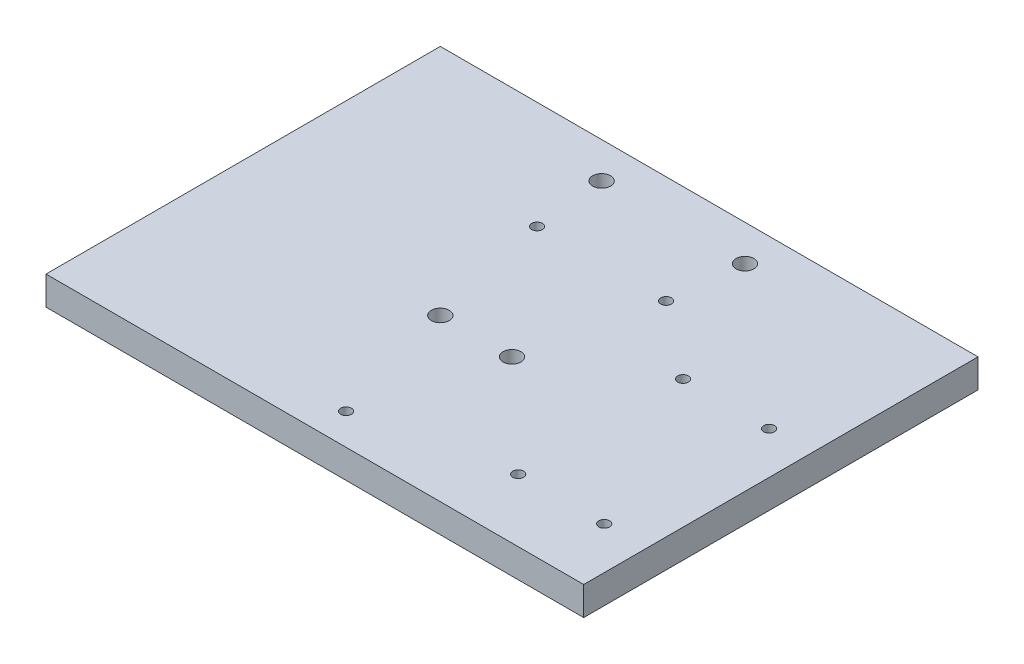
SolidWorks part; units mm, degrees
ref_plane "Front Plane" through (0, 0, 0) normal (0, 0, 1) x (1, 0, 0)
ref_plane "Top Plane" through (0, 0, 0) normal (0, 1, 0) x (1, 0, 0)
ref_plane "Right Plane" through (0, 0, 0) normal (1, 0, 0) x (0, 0, -1)
sketch "Sketch1" plane through (0, 0, 0) normal (0, 1, 0) x (1, 0, 0)
  line L0 (-75, 0) -> (75, 0)
  line L1 (-75, 0) -> (-75, -110)
  line L2 (-75, -110) -> (75, -110)
  line L3 (75, -110) -> (75, 0)
  line L4 (0, 0) -> (0, -20) construction
  line L5 (10, -20) -> (-10, -20) construction
  line L6 (-10, -20) -> (-10, -65) construction
  line L7 (10, -20) -> (10, -65) construction
  line L8 (0, -10) -> (-20, -10) construction
  circle A1 centre (-10, -65) radius 2.5
  circle A2 centre (10, -65) radius 2.5
  circle A3 centre (-20, -10) radius 2.5
  circle A4 centre (20, -10) radius 2.5
  point P4 (0, 0)
  dimension "D6" = 5
  dimension "D7" = 5
  dimension "D11" = 5
  dimension "D1" = 150
  dimension "D2" = 110
  dimension "D3" = 20
  dimension "D4" = 10
  dimension "D8" = 45
  dimension "D9" = 45
  dimension "D10" = 20
extrude "Boss-Extrude1" add sketch "Sketch1" along normal blind 8
sketch "Sketch3" plane through (0, 8, 0) normal (0, 1, 0) x (1, 0, 0)
  line L0 (0, 0) -> (0, -30) construction
  line L2 (18, -30) -> (-18, -30) construction
  line L3 (75, 0) -> (-75, 0) construction
  line L4 (0, -30) -> (0, -101.3) construction
  circle A0 centre (-18, -30) radius 1.5
  circle A1 centre (18, -30) radius 1.5
  circle A2 centre (0, -101.3) radius 1.5
  point P8 (0, -30)
  dimension "D3" = 3
  dimension "D5" = 3
  dimension "D1" = 18
  dimension "D2" = 30
  dimension "D4" = 71.3
extrude "Cut-Extrude1" cut sketch "Sketch3" against normal blind 8
sketch "Sketch4" plane through (0, 8, 0) normal (0, 1, 0) x (1, 0, 0)
  line L0 (0, 0) -> (0, -46.4925) construction
  line L1 (0, -46.4925) -> (39.2157, -46.4925) construction
  line L2 (39.2157, -46.4925) -> (63.2157, -46.4925) construction
  line L3 (0, -46.4925) -> (0, -92.4925) construction
  line L4 (0, -92.4925) -> (63.2157, -92.4925) construction
  line L5 (39.2157, -46.4925) -> (39.2157, -92.4925) construction
  circle A0 centre (39.2157, -46.4925) radius 1.5
  circle A1 centre (63.2157, -46.4925) radius 1.5
  circle A2 centre (39.2157, -92.4925) radius 1.5
  circle A3 centre (63.2157, -92.4925) radius 1.5
  dimension "D1" = 3
  dimension "D2" = 3
  dimension "D5" = 3
  dimension "D6" = 3
  dimension "D3" = 24
  dimension "D4" = 46
extrude "Cut-Extrude2" cut sketch "Sketch4" against normal blind 8
sketch "Sketch5" plane through (0, 0, 0) normal (0, -1, 0) x (1, 0, 0)
  line L1 (-5, 96.3) -> (5, 96.3)
  line L2 (-5, 96.3) -> (-5, 106.3)
  line L3 (-5, 106.3) -> (5, 106.3)
  line L4 (5, 96.3) -> (5, 106.3)
  line L5 (-5, 96.3) -> (5, 106.3) construction
  line L6 (-5, 106.3) -> (5, 96.3) construction
  line L7 (34.2157, 87.4925) -> (44.2157, 87.4925)
  line L8 (34.2157, 87.4925) -> (34.2157, 97.4925)
  line L9 (34.2157, 97.4925) -> (44.2157, 97.4925)
  line L10 (44.2157, 87.4925) -> (44.2157, 97.4925)
  line L11 (34.2157, 87.4925) -> (44.2157, 97.4925) construction
  line L12 (34.2157, 97.4925) -> (44.2157, 87.4925) construction
  line L13 (58.2157, 87.4925) -> (68.2157, 87.4925)
  line L14 (58.2157, 87.4925) -> (58.2157, 97.4925)
  line L15 (58.2157, 97.4925) -> (68.2157, 97.4925)
  line L16 (68.2157, 87.4925) -> (68.2157, 97.4925)
  line L17 (58.2157, 87.4925) -> (68.2157, 97.4925) construction
  line L18 (58.2157, 97.4925) -> (68.2157, 87.4925) construction
  line L19 (58.2157, 41.4925) -> (68.2157, 41.4925)
  line L20 (58.2157, 41.4925) -> (58.2157, 51.4925)
  line L21 (58.2157, 51.4925) -> (68.2157, 51.4925)
  line L22 (68.2157, 41.4925) -> (68.2157, 51.4925)
  line L23 (58.2157, 41.4925) -> (68.2157, 51.4925) construction
  line L24 (58.2157, 51.4925) -> (68.2157, 41.4925) construction
  line L25 (34.2157, 41.4925) -> (44.2157, 41.4925)
  line L26 (34.2157, 41.4925) -> (34.2157, 51.4925)
  line L27 (34.2157, 51.4925) -> (44.2157, 51.4925)
  line L28 (44.2157, 41.4925) -> (44.2157, 51.4925)
  line L29 (34.2157, 41.4925) -> (44.2157, 51.4925) construction
  line L30 (34.2157, 51.4925) -> (44.2157, 41.4925) construction
  line L31 (-23, 25) -> (-13, 25)
  line L32 (-23, 25) -> (-23, 35)
  line L33 (-23, 35) -> (-13, 35)
  line L34 (-13, 25) -> (-13, 35)
  line L35 (-23, 25) -> (-13, 35) construction
  line L36 (-23, 35) -> (-13, 25) construction
  line L37 (13, 25) -> (23, 25)
  line L38 (13, 25) -> (13, 35)
  line L39 (13, 35) -> (23, 35)
  line L40 (23, 25) -> (23, 35)
  line L41 (13, 25) -> (23, 35) construction
  line L42 (13, 35) -> (23, 25) construction
  point P0 (0, 101.3)
  point P6 (39.2157, 92.4925)
  point P12 (63.2157, 92.4925)
  point P18 (63.2157, 46.4925)
  point P24 (39.2157, 46.4925)
  point P30 (-18, 30)
  point P36 (18, 30)
  dimension "D1" = 10
  dimension "D2" = 10
  dimension "D3" = 10
  dimension "D4" = 10
  dimension "D5" = 10
  dimension "D6" = 10
  dimension "D7" = 10
  dimension "D8" = 10
  dimension "D9" = 10
  dimension "D10" = 10
  dimension "D11" = 10
  dimension "D12" = 10
  dimension "D13" = 10
  dimension "D14" = 10
extrude "Cut-Extrude3" cut sketch "Sketch5" against normal blind 3
